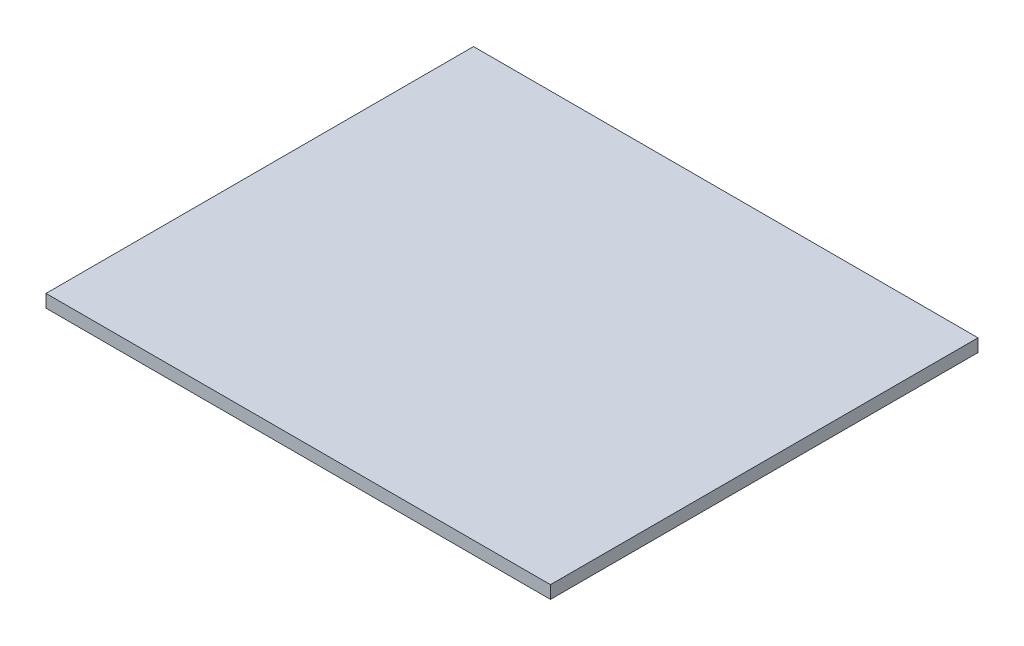
SolidWorks part; units mm, degrees
ref_plane "Front Plane" through (0, 0, 0) normal (0, 0, 1) x (1, 0, 0)
ref_plane "Top Plane" through (0, 0, 0) normal (0, 1, 0) x (1, 0, 0)
ref_plane "Right Plane" through (0, 0, 0) normal (1, 0, 0) x (0, 0, -1)
sketch "Sketch1" plane through (0, 0, 0) normal (0, 1, 0) x (1, 0, 0)
  line L1 (-39.35, 33.35) -> (39.35, 33.35)
  line L2 (-39.35, 33.35) -> (-39.35, -33.35)
  line L3 (-39.35, -33.35) -> (39.35, -33.35)
  line L4 (39.35, 33.35) -> (39.35, -33.35)
  line L5 (-39.35, 33.35) -> (39.35, -33.35) construction
  line L6 (-39.35, -33.35) -> (39.35, 33.35) construction
  point P0 (0, 0)
  dimension "D1" = 66.7
  dimension "D2" = 78.7
extrude "Boss-Extrude1" add sketch "Sketch1" along normal blind 2
sketch "Sketch2" plane through (0, 2, 0) normal (0, 1, 0) x (1, 0, 0)
  line L0 (39.35, 33.35) -> (-39.35, 33.35) construction
  line L1 (-39.35, 33.35) -> (-39.35, -33.35) construction
  line L2 (-39.35, -33.35) -> (39.35, -33.35) construction
  line L3 (0, -55) -> (0, 55) construction
  line L4 (-36.35, 31.85) -> (-29.0965, 31.85) construction
  circle A0 centre (-36.35, 30.35) radius 1.5
  circle A1 centre (-36.35, -30.35) radius 2
  circle A2 centre (36.35, -30.35) radius 2
  circle A3 centre (36.35, 30.35) radius 1.5
  dimension "D1" = 3
  dimension "D2" = 3
  dimension "D4" = 4
  dimension "D3" = 3
  dimension "D5" = 3
